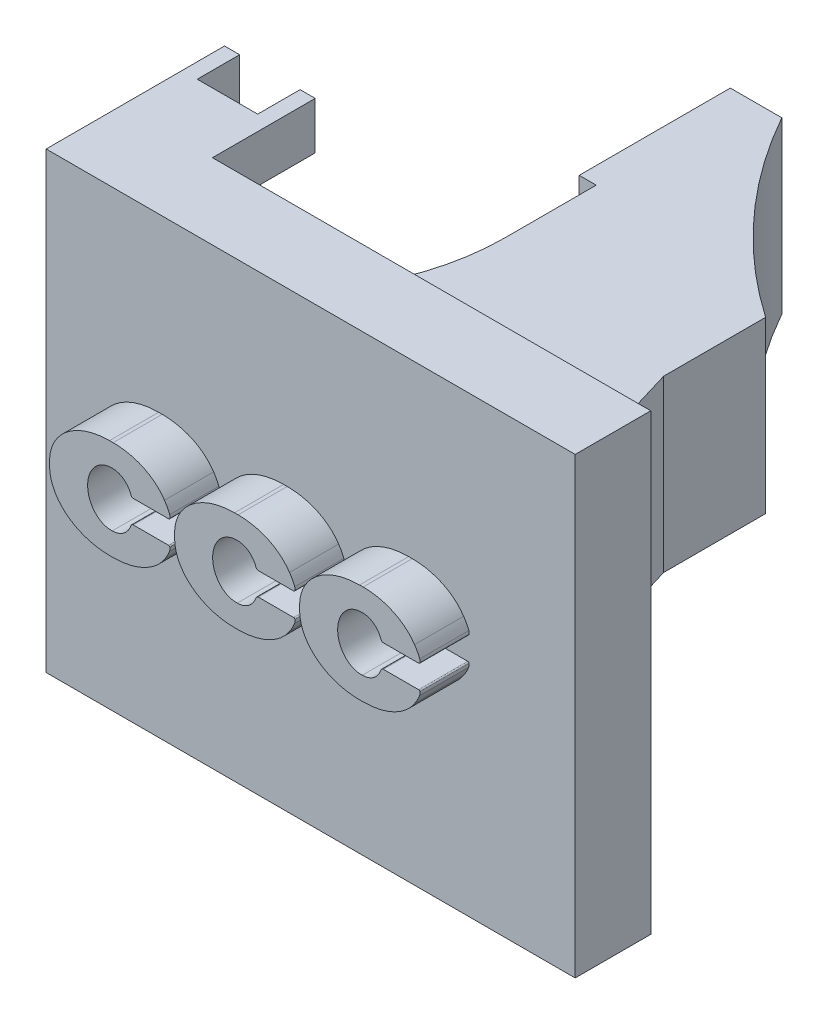
SolidWorks part; units mm, degrees
ref_plane "Front Plane" through (0, 0, 0) normal (0, 0, 1) x (1, 0, 0)
ref_plane "Top Plane" through (0, 0, 0) normal (0, 1, 0) x (1, 0, 0)
ref_plane "Right Plane" through (0, 0, 0) normal (1, 0, 0) x (0, 0, -1)
sketch "Sketch1" plane through (0, 0, 0) normal (0, 0, 1) x (1, 0, 0)
  line L1 (-7.5, 6) -> (7.5, 6)
  line L2 (-7.5, 6) -> (-7.5, -6)
  line L3 (-7.5, -6) -> (7.5, -6)
  line L4 (7.5, 6) -> (7.5, -6)
  line L5 (-7.5, 6) -> (7.5, -6) construction
  line L6 (-7.5, -6) -> (7.5, 6) construction
  point P0 (0, 0)
  dimension "D1" = 15
  dimension "D2" = 12
extrude "Boss-Extrude1" add sketch "Sketch1" along normal blind 2
sketch "Sketch2" plane through (0, 0, 2) normal (0, 0, 1) x (1, 0, 0)
  line L0 (-0.5835, 0.4438) -> (0.3524, 0.4438)
  line L1 (-1.1209, 1.4546) -> (-1.2145, 1.4546)
  line L2 (-2.8001, 0.2034) -> (-2.8001, 0.0733)
  line L3 (-1.2145, -1.1779) -> (-1.1209, -1.1779)
  line L4 (0.3478, -0.1633) -> (-0.5835, -0.1633)
  line L5 (-3.8918, 0.4438) -> (-2.956, 0.4438)
  line L6 (-4.4292, 1.4546) -> (-4.5228, 1.4546)
  line L7 (-6.1084, 0.2034) -> (-6.1084, 0.0733)
  line L8 (-4.5228, -1.1779) -> (-4.4292, -1.1779)
  line L9 (-2.9605, -0.1633) -> (-3.8918, -0.1633)
  line L10 (2.7248, 0.4438) -> (3.6607, 0.4438)
  line L11 (2.1874, 1.4546) -> (2.0938, 1.4546)
  line L12 (0.5082, 0.2034) -> (0.5082, 0.0733)
  line L13 (2.0938, -1.1779) -> (2.1874, -1.1779)
  line L14 (3.6561, -0.1633) -> (2.7248, -0.1633)
  arc A0 (-0.6452, 0.4874) -> (-0.5835, 0.4438) centre (-0.5835, 0.5092) ccw
  arc A1 (0.3524, 0.4438) -> (0.3816, 0.4686) centre (0.3479, 0.4787) ccw
  arc A2 (0.3816, 0.4686) -> (0.3774, 0.5561) centre (0.201, 0.5038) ccw
  arc A3 (0.3774, 0.5561) -> (0.2402, 0.8134) centre (-0.7046, 0.1445) ccw
  arc A4 (0.2402, -0.5368) -> (0.3727, -0.2904) centre (-0.6952, 0.1249) ccw
  arc A5 (0.3727, -0.2904) -> (0.3825, -0.1925) centre (0.2012, -0.2237) ccw
  arc A6 (0.3825, -0.1925) -> (0.3478, -0.1633) centre (0.3478, -0.1984) ccw
  arc A7 (-0.5835, -0.1633) -> (-0.6452, -0.2069) centre (-0.5835, -0.2287) ccw
  arc A8 (-3.9535, 0.4874) -> (-3.8918, 0.4438) centre (-3.8918, 0.5092) ccw
  arc A9 (-2.956, 0.4438) -> (-2.9267, 0.4686) centre (-2.9604, 0.4787) ccw
  arc A10 (-2.9267, 0.4686) -> (-2.9309, 0.5561) centre (-3.1073, 0.5038) ccw
  arc A11 (-2.9309, 0.5561) -> (-3.0681, 0.8134) centre (-4.0129, 0.1445) ccw
  arc A12 (-3.0681, -0.5368) -> (-2.9356, -0.2904) centre (-4.0035, 0.1249) ccw
  arc A13 (-2.9356, -0.2904) -> (-2.9258, -0.1925) centre (-3.1071, -0.2237) ccw
  arc A14 (-2.9258, -0.1925) -> (-2.9605, -0.1633) centre (-2.9605, -0.1984) ccw
  arc A15 (-3.8918, -0.1633) -> (-3.9535, -0.2069) centre (-3.8918, -0.2287) ccw
  arc A16 (2.6631, 0.4874) -> (2.7248, 0.4438) centre (2.7248, 0.5092) ccw
  arc A17 (3.6607, 0.4438) -> (3.6899, 0.4686) centre (3.6562, 0.4787) ccw
  arc A18 (3.6899, 0.4686) -> (3.6857, 0.5561) centre (3.5093, 0.5038) ccw
  arc A19 (3.6857, 0.5561) -> (3.5485, 0.8134) centre (2.6037, 0.1445) ccw
  arc A20 (3.5485, -0.5368) -> (3.681, -0.2904) centre (2.6131, 0.1249) ccw
  arc A21 (3.681, -0.2904) -> (3.6908, -0.1925) centre (3.5095, -0.2237) ccw
  arc A22 (3.6908, -0.1925) -> (3.6561, -0.1633) centre (3.6561, -0.1984) ccw
  arc A23 (2.7248, -0.1633) -> (2.6631, -0.2069) centre (2.7248, -0.2287) ccw
  ellipse E0 centre (-1.1734, 0.1385) end of major axis (-1.177, 0.8556) minor radius 0.6209 (-1.2015, 0.8549) -> (-1.1417, -0.5777) ccw
  ellipse E1 centre (-1.2295, 0.1385) end of major axis (-1.5121, -0.5431) minor radius 0.6039 (-0.6452, 0.4874) -> (-1.2015, 0.8549) ccw
  ellipse E2 centre (-1.2429, 0.1529) end of major axis (-2.8857, -0.0922) minor radius 1.2925 (0.2402, 0.8134) -> (-1.1209, 1.4546) ccw
  ellipse E3 centre (-1.1521, 0.1542) end of major axis (0.4928, 0.0248) minor radius 1.2979 (-1.2145, 1.4546) -> (-2.8001, 0.2034) ccw
  ellipse E4 centre (-1.1521, 0.1225) end of major axis (0.4928, 0.2518) minor radius 1.2979 (-2.8001, 0.0733) -> (-1.2145, -1.1779) ccw
  ellipse E5 centre (-1.2429, 0.1238) end of major axis (-2.8857, 0.3689) minor radius 1.2925 (-1.1209, -1.1779) -> (0.2402, -0.5368) ccw
  ellipse E6 centre (-1.2295, 0.1421) end of major axis (-0.9469, -0.5396) minor radius 0.6039 (-1.1417, -0.5777) -> (-0.6452, -0.2069) ccw
  ellipse E7 centre (-4.5378, 0.1385) end of major axis (-4.8204, -0.5431) minor radius 0.6039 (-3.9535, 0.4874) -> (-4.5098, 0.8549) ccw
  ellipse E8 centre (-4.5512, 0.1529) end of major axis (-6.194, -0.0922) minor radius 1.2925 (-3.0681, 0.8134) -> (-4.4292, 1.4546) ccw
  ellipse E9 centre (-4.4604, 0.1542) end of major axis (-6.1053, 0.2835) minor radius 1.2979 (-4.5228, 1.4546) -> (-6.1084, 0.2034) ccw
  ellipse E10 centre (-4.4604, 0.1225) end of major axis (-6.1053, -0.0069) minor radius 1.2979 (-6.1084, 0.0733) -> (-4.5228, -1.1779) ccw
  ellipse E11 centre (-4.5512, 0.1238) end of major axis (-6.194, 0.3689) minor radius 1.2925 (-4.4292, -1.1779) -> (-3.0681, -0.5368) ccw
  ellipse E12 centre (-4.5378, 0.1421) end of major axis (-4.2552, -0.5396) minor radius 0.6039 (-4.45, -0.5777) -> (-3.9535, -0.2069) ccw
  ellipse E13 centre (-4.4817, 0.1385) end of major axis (-4.4853, 0.8556) minor radius 0.6209 (-4.5098, 0.8549) -> (-4.45, -0.5777) ccw
  ellipse E14 centre (2.1349, 0.1385) end of major axis (2.1385, -0.5786) minor radius 0.6209 (2.1069, 0.8549) -> (2.1666, -0.5777) ccw
  ellipse E15 centre (2.0788, 0.1385) end of major axis (2.3614, 0.8201) minor radius 0.6039 (2.6631, 0.4874) -> (2.1069, 0.8549) ccw
  ellipse E16 centre (2.0654, 0.1529) end of major axis (3.7082, 0.3981) minor radius 1.2925 (3.5485, 0.8134) -> (2.1874, 1.4546) ccw
  ellipse E17 centre (2.1562, 0.1542) end of major axis (0.5113, 0.2835) minor radius 1.2979 (2.0938, 1.4546) -> (0.5082, 0.2034) ccw
  ellipse E18 centre (2.1562, 0.1225) end of major axis (3.8011, 0.2518) minor radius 1.2979 (0.5082, 0.0733) -> (2.0938, -1.1779) ccw
  ellipse E19 centre (2.0654, 0.1238) end of major axis (0.4226, 0.3689) minor radius 1.2925 (2.1874, -1.1779) -> (3.5485, -0.5368) ccw
  ellipse E20 centre (2.0788, 0.1421) end of major axis (2.3614, -0.5396) minor radius 0.6039 (2.1666, -0.5777) -> (2.6631, -0.2069) ccw
extrude "Boss-Extrude2" add sketch "Sketch2" along normal blind 2
sketch "Sketch3" plane through (0, 0, 0) normal (0, 1, 0) x (1, 0, 0)
  line L0 (7.5, 0) -> (-7.5, 0) construction
  line L1 (-5.267, 0.6593) -> (-4.0407, 2.642)
  line L2 (-3.1435, 5.7982) -> (-3.1435, 7.8852)
  line L3 (2.1273, 7.8852) -> (2.1273, 4.7149)
  line L4 (3.2287, 0) -> (3.2287, 1.0429)
  line L5 (2.1273, 4.7149) -> (3.2287, 1.0429)
  line L6 (-5.267, 0) -> (-5.267, 0.6593)
  line L7 (-1.1926, -2) -> (-1.1926, 1.9881) construction
  line L9 (-5.267, 0) -> (3.2287, 0)
  line L11 (-3.1435, 7.8852) -> (-3.1435, 12.1994)
  line L12 (-3.1435, 12.1994) -> (2.1273, 12.1994)
  line L16 (2.1273, 12.1994) -> (2.1273, 7.8852)
  arc A0 (-4.0407, 2.642) -> (-3.1435, 5.7982) centre (-9.1435, 5.7982) ccw
  dimension "D1" = 6
extrude "Boss-Extrude3" add sketch "Sketch3" along normal mid plane 4.5
sketch "Sketch4" plane through (7.5, 0, 0) normal (1, 0, 0) x (0, 0, -1)
  line L4 (0, -6) -> (0, 6)
  line L5 (0, 6) -> (-2, 6)
  line L6 (-2, 6) -> (-2, -6)
  line L7 (-2, -6) -> (0, -6)
  line L8 (0, -6) -> (0, 6)
  line L9 (0, 6) -> (-2, 6)
  line L10 (-2, 6) -> (-2, -6)
  line L11 (-2, -6) -> (0, -6)
  dimension "D1" = 0
extrude "Cut-Extrude1" cut sketch "Sketch4" against normal blind 1
sketch "Sketch6" plane through (0, 0, 4) normal (0, 0, 1) x (1, 0, 0)
  line L0 (2.7248, 0.4438) -> (3.6607, 0.4438) construction
  line L1 (2.1874, 1.4546) -> (2.0938, 1.4546) construction
  line L2 (0.5082, 0.2034) -> (0.5082, 0.0733) construction
  line L3 (2.0938, -1.1779) -> (2.1874, -1.1779) construction
  line L4 (3.6561, -0.1633) -> (2.7248, -0.1633) construction
  line L5 (-0.5835, 0.4438) -> (0.3524, 0.4438) construction
  line L6 (-1.1209, 1.4546) -> (-1.2145, 1.4546) construction
  line L7 (-2.8001, 0.2034) -> (-2.8001, 0.0733) construction
  line L8 (-1.2145, -1.1779) -> (-1.1209, -1.1779) construction
  line L9 (0.3478, -0.1633) -> (-0.5835, -0.1633) construction
  line L10 (-3.8918, 0.4438) -> (-2.956, 0.4438) construction
  line L11 (-4.4292, 1.4546) -> (-4.5228, 1.4546) construction
  line L12 (-6.1084, 0.2034) -> (-6.1084, 0.0733) construction
  line L13 (-4.5228, -1.1779) -> (-4.4292, -1.1779) construction
  line L14 (-2.9605, -0.1633) -> (-3.8918, -0.1633) construction
  line L15 (2.7248, 0.4438) -> (3.6607, 0.4438)
  line L16 (2.1874, 1.4546) -> (2.0938, 1.4546)
  line L17 (0.5082, 0.2034) -> (0.5082, 0.0733)
  line L18 (2.0938, -1.1779) -> (2.1874, -1.1779)
  line L19 (3.6561, -0.1633) -> (2.7248, -0.1633)
  line L20 (-0.5835, 0.4438) -> (0.3524, 0.4438)
  line L21 (-1.1209, 1.4546) -> (-1.2145, 1.4546)
  line L22 (-2.8001, 0.2034) -> (-2.8001, 0.0733)
  line L23 (-1.2145, -1.1779) -> (-1.1209, -1.1779)
  line L24 (0.3478, -0.1633) -> (-0.5835, -0.1633)
  line L25 (-3.8918, 0.4438) -> (-2.956, 0.4438)
  line L26 (-4.4292, 1.4546) -> (-4.5228, 1.4546)
  line L27 (-6.1084, 0.2034) -> (-6.1084, 0.0733)
  line L28 (-4.5228, -1.1779) -> (-4.4292, -1.1779)
  line L29 (-2.9605, -0.1633) -> (-3.8918, -0.1633)
  arc A0 (2.6631, 0.4874) -> (2.7248, 0.4438) centre (2.7248, 0.5092) ccw construction
  arc A1 (3.6607, 0.4438) -> (3.6899, 0.4686) centre (3.6562, 0.4787) ccw construction
  arc A2 (3.6899, 0.4686) -> (3.6857, 0.5561) centre (3.5093, 0.5038) ccw construction
  arc A3 (3.6857, 0.5561) -> (3.5485, 0.8134) centre (2.6037, 0.1445) ccw construction
  arc A4 (3.5485, -0.5368) -> (3.681, -0.2904) centre (2.6131, 0.1249) ccw construction
  arc A5 (3.681, -0.2904) -> (3.6908, -0.1925) centre (3.5095, -0.2237) ccw construction
  arc A6 (3.6908, -0.1925) -> (3.6561, -0.1633) centre (3.6561, -0.1984) ccw construction
  arc A7 (2.7248, -0.1633) -> (2.6631, -0.2069) centre (2.7248, -0.2287) ccw construction
  arc A8 (-0.6452, 0.4874) -> (-0.5835, 0.4438) centre (-0.5835, 0.5092) ccw construction
  arc A9 (0.3524, 0.4438) -> (0.3816, 0.4686) centre (0.3479, 0.4787) ccw construction
  arc A10 (0.3816, 0.4686) -> (0.3774, 0.5561) centre (0.201, 0.5038) ccw construction
  arc A11 (0.3774, 0.5561) -> (0.2402, 0.8134) centre (-0.7046, 0.1445) ccw construction
  arc A12 (0.2402, -0.5368) -> (0.3727, -0.2904) centre (-0.6952, 0.1249) ccw construction
  arc A13 (0.3727, -0.2904) -> (0.3825, -0.1925) centre (0.2012, -0.2237) ccw construction
  arc A14 (0.3825, -0.1925) -> (0.3478, -0.1633) centre (0.3478, -0.1984) ccw construction
  arc A15 (-0.5835, -0.1633) -> (-0.6452, -0.2069) centre (-0.5835, -0.2287) ccw construction
  arc A16 (-3.9535, 0.4874) -> (-3.8918, 0.4438) centre (-3.8918, 0.5092) ccw construction
  arc A17 (-2.956, 0.4438) -> (-2.9267, 0.4686) centre (-2.9604, 0.4787) ccw construction
  arc A18 (-2.9267, 0.4686) -> (-2.9309, 0.5561) centre (-3.1073, 0.5038) ccw construction
  arc A19 (-2.9309, 0.5561) -> (-3.0681, 0.8134) centre (-4.0129, 0.1445) ccw construction
  arc A20 (-3.0681, -0.5368) -> (-2.9356, -0.2904) centre (-4.0035, 0.1249) ccw construction
  arc A21 (-2.9356, -0.2904) -> (-2.9258, -0.1925) centre (-3.1071, -0.2237) ccw construction
  arc A22 (-2.9258, -0.1925) -> (-2.9605, -0.1633) centre (-2.9605, -0.1984) ccw construction
  arc A23 (-3.8918, -0.1633) -> (-3.9535, -0.2069) centre (-3.8918, -0.2287) ccw construction
  arc A24 (2.6631, 0.4874) -> (2.7248, 0.4438) centre (2.7248, 0.5092) ccw
  arc A25 (3.6607, 0.4438) -> (3.6899, 0.4686) centre (3.6562, 0.4787) ccw
  arc A26 (3.6899, 0.4686) -> (3.6857, 0.5561) centre (3.5093, 0.5038) ccw
  arc A27 (3.6857, 0.5561) -> (3.5485, 0.8134) centre (2.6037, 0.1445) ccw
  arc A28 (3.5485, -0.5368) -> (3.681, -0.2904) centre (2.6131, 0.1249) ccw
  arc A29 (3.681, -0.2904) -> (3.6908, -0.1925) centre (3.5095, -0.2237) ccw
  arc A30 (3.6908, -0.1925) -> (3.6561, -0.1633) centre (3.6561, -0.1984) ccw
  arc A31 (2.7248, -0.1633) -> (2.6631, -0.2069) centre (2.7248, -0.2287) ccw
  arc A32 (-0.6452, 0.4874) -> (-0.5835, 0.4438) centre (-0.5835, 0.5092) ccw
  arc A33 (0.3524, 0.4438) -> (0.3816, 0.4686) centre (0.3479, 0.4787) ccw
  arc A34 (0.3816, 0.4686) -> (0.3774, 0.5561) centre (0.201, 0.5038) ccw
  arc A35 (0.3774, 0.5561) -> (0.2402, 0.8134) centre (-0.7046, 0.1445) ccw
  arc A36 (0.2402, -0.5368) -> (0.3727, -0.2904) centre (-0.6952, 0.1249) ccw
  arc A37 (0.3727, -0.2904) -> (0.3825, -0.1925) centre (0.2012, -0.2237) ccw
  arc A38 (0.3825, -0.1925) -> (0.3478, -0.1633) centre (0.3478, -0.1984) ccw
  arc A39 (-0.5835, -0.1633) -> (-0.6452, -0.2069) centre (-0.5835, -0.2287) ccw
  arc A40 (-3.9535, 0.4874) -> (-3.8918, 0.4438) centre (-3.8918, 0.5092) ccw
  arc A41 (-2.956, 0.4438) -> (-2.9267, 0.4686) centre (-2.9604, 0.4787) ccw
  arc A42 (-2.9267, 0.4686) -> (-2.9309, 0.5561) centre (-3.1073, 0.5038) ccw
  arc A43 (-2.9309, 0.5561) -> (-3.0681, 0.8134) centre (-4.0129, 0.1445) ccw
  arc A44 (-3.0681, -0.5368) -> (-2.9356, -0.2904) centre (-4.0035, 0.1249) ccw
  arc A45 (-2.9356, -0.2904) -> (-2.9258, -0.1925) centre (-3.1071, -0.2237) ccw
  arc A46 (-2.9258, -0.1925) -> (-2.9605, -0.1633) centre (-2.9605, -0.1984) ccw
  arc A47 (-3.8918, -0.1633) -> (-3.9535, -0.2069) centre (-3.8918, -0.2287) ccw
  ellipse E0 centre (2.0788, 0.1385) end of major axis (1.7962, -0.5431) minor radius 0.6039 (2.6631, 0.4874) -> (2.1069, 0.8549) ccw construction
  ellipse E1 centre (2.0654, 0.1529) end of major axis (0.4226, -0.0922) minor radius 1.2925 (3.5485, 0.8134) -> (2.1874, 1.4546) ccw construction
  ellipse E2 centre (2.1562, 0.1542) end of major axis (0.5113, 0.2835) minor radius 1.2979 (2.0938, 1.4546) -> (0.5082, 0.2034) ccw construction
  ellipse E3 centre (2.1562, 0.1225) end of major axis (3.8011, 0.2518) minor radius 1.2979 (0.5082, 0.0733) -> (2.0938, -1.1779) ccw construction
  ellipse E4 centre (2.0654, 0.1238) end of major axis (0.4226, 0.3689) minor radius 1.2925 (2.1874, -1.1779) -> (3.5485, -0.5368) ccw construction
  ellipse E5 centre (2.0788, 0.1421) end of major axis (2.3614, -0.5396) minor radius 0.6039 (2.1666, -0.5777) -> (2.6631, -0.2069) ccw construction
  ellipse E6 centre (2.1349, 0.1385) end of major axis (2.1385, -0.5786) minor radius 0.6209 (2.1069, 0.8549) -> (2.1666, -0.5777) ccw construction
  ellipse E7 centre (-1.2295, 0.1385) end of major axis (-1.5121, -0.5431) minor radius 0.6039 (-0.6452, 0.4874) -> (-1.2015, 0.8549) ccw construction
  ellipse E8 centre (-1.2429, 0.1529) end of major axis (0.3999, 0.3981) minor radius 1.2925 (0.2402, 0.8134) -> (-1.1209, 1.4546) ccw construction
  ellipse E9 centre (-1.1521, 0.1542) end of major axis (-2.797, 0.2835) minor radius 1.2979 (-1.2145, 1.4546) -> (-2.8001, 0.2034) ccw construction
  ellipse E10 centre (-1.1521, 0.1225) end of major axis (0.4928, 0.2518) minor radius 1.2979 (-2.8001, 0.0733) -> (-1.2145, -1.1779) ccw construction
  ellipse E11 centre (-1.2429, 0.1238) end of major axis (0.3999, -0.1214) minor radius 1.2925 (-1.1209, -1.1779) -> (0.2402, -0.5368) ccw construction
  ellipse E12 centre (-1.2295, 0.1421) end of major axis (-0.9469, -0.5396) minor radius 0.6039 (-1.1417, -0.5777) -> (-0.6452, -0.2069) ccw construction
  ellipse E13 centre (-1.1734, 0.1385) end of major axis (-1.1698, -0.5786) minor radius 0.6209 (-1.2015, 0.8549) -> (-1.1417, -0.5777) ccw construction
  ellipse E14 centre (-4.5378, 0.1385) end of major axis (-4.8204, -0.5431) minor radius 0.6039 (-3.9535, 0.4874) -> (-4.5098, 0.8549) ccw construction
  ellipse E15 centre (-4.5512, 0.1529) end of major axis (-2.9084, 0.3981) minor radius 1.2925 (-3.0681, 0.8134) -> (-4.4292, 1.4546) ccw construction
  ellipse E16 centre (-4.4604, 0.1542) end of major axis (-6.1053, 0.2835) minor radius 1.2979 (-4.5228, 1.4546) -> (-6.1084, 0.2034) ccw construction
  ellipse E17 centre (-4.4604, 0.1225) end of major axis (-2.8155, 0.2518) minor radius 1.2979 (-6.1084, 0.0733) -> (-4.5228, -1.1779) ccw construction
  ellipse E18 centre (-4.5512, 0.1238) end of major axis (-6.194, 0.3689) minor radius 1.2925 (-4.4292, -1.1779) -> (-3.0681, -0.5368) ccw construction
  ellipse E19 centre (-4.5378, 0.1421) end of major axis (-4.2552, -0.5396) minor radius 0.6039 (-4.45, -0.5777) -> (-3.9535, -0.2069) ccw construction
  ellipse E20 centre (-4.4817, 0.1385) end of major axis (-4.4781, -0.5786) minor radius 0.6209 (-4.5098, 0.8549) -> (-4.45, -0.5777) ccw construction
  ellipse E21 centre (2.0788, 0.1385) end of major axis (1.7962, -0.5431) minor radius 0.6039 (2.6631, 0.4874) -> (2.1069, 0.8549) ccw
  ellipse E22 centre (2.0654, 0.1529) end of major axis (3.7082, 0.3981) minor radius 1.2925 (3.5485, 0.8134) -> (2.1874, 1.4546) ccw
  ellipse E23 centre (2.1562, 0.1542) end of major axis (0.5113, 0.2835) minor radius 1.2979 (2.0938, 1.4546) -> (0.5082, 0.2034) ccw
  ellipse E24 centre (2.1562, 0.1225) end of major axis (3.8011, 0.2518) minor radius 1.2979 (0.5082, 0.0733) -> (2.0938, -1.1779) ccw
  ellipse E25 centre (2.0654, 0.1238) end of major axis (0.4226, 0.3689) minor radius 1.2925 (2.1874, -1.1779) -> (3.5485, -0.5368) ccw
  ellipse E26 centre (2.0788, 0.1421) end of major axis (2.3614, -0.5396) minor radius 0.6039 (2.1666, -0.5777) -> (2.6631, -0.2069) ccw
  ellipse E27 centre (2.1349, 0.1385) end of major axis (2.1385, -0.5786) minor radius 0.6209 (2.1069, 0.8549) -> (2.1666, -0.5777) ccw
  ellipse E28 centre (-1.2295, 0.1385) end of major axis (-1.5121, -0.5431) minor radius 0.6039 (-0.6452, 0.4874) -> (-1.2015, 0.8549) ccw
  ellipse E29 centre (-1.2429, 0.1529) end of major axis (0.3999, 0.3981) minor radius 1.2925 (0.2402, 0.8134) -> (-1.1209, 1.4546) ccw
  ellipse E30 centre (-1.1521, 0.1542) end of major axis (-2.797, 0.2835) minor radius 1.2979 (-1.2145, 1.4546) -> (-2.8001, 0.2034) ccw
  ellipse E31 centre (-1.1521, 0.1225) end of major axis (0.4928, 0.2518) minor radius 1.2979 (-2.8001, 0.0733) -> (-1.2145, -1.1779) ccw
  ellipse E32 centre (-1.2429, 0.1238) end of major axis (-2.8857, 0.3689) minor radius 1.2925 (-1.1209, -1.1779) -> (0.2402, -0.5368) ccw
  ellipse E33 centre (-1.2295, 0.1421) end of major axis (-0.9469, -0.5396) minor radius 0.6039 (-1.1417, -0.5777) -> (-0.6452, -0.2069) ccw
  ellipse E34 centre (-1.1734, 0.1385) end of major axis (-1.1698, -0.5786) minor radius 0.6209 (-1.2015, 0.8549) -> (-1.1417, -0.5777) ccw
  ellipse E35 centre (-4.5378, 0.1385) end of major axis (-4.8204, -0.5431) minor radius 0.6039 (-3.9535, 0.4874) -> (-4.5098, 0.8549) ccw
  ellipse E36 centre (-4.5512, 0.1529) end of major axis (-2.9084, 0.3981) minor radius 1.2925 (-3.0681, 0.8134) -> (-4.4292, 1.4546) ccw
  ellipse E37 centre (-4.4604, 0.1542) end of major axis (-6.1053, 0.2835) minor radius 1.2979 (-4.5228, 1.4546) -> (-6.1084, 0.2034) ccw
  ellipse E38 centre (-4.4604, 0.1225) end of major axis (-2.8155, 0.2518) minor radius 1.2979 (-6.1084, 0.0733) -> (-4.5228, -1.1779) ccw
  ellipse E39 centre (-4.5512, 0.1238) end of major axis (-6.194, 0.3689) minor radius 1.2925 (-4.4292, -1.1779) -> (-3.0681, -0.5368) ccw
  ellipse E40 centre (-4.5378, 0.1421) end of major axis (-4.2552, -0.5396) minor radius 0.6039 (-4.45, -0.5777) -> (-3.9535, -0.2069) ccw
  ellipse E41 centre (-4.4817, 0.1385) end of major axis (-4.4781, -0.5786) minor radius 0.6209 (-4.5098, 0.8549) -> (-4.45, -0.5777) ccw
extrude "Cut-Extrude3" cut sketch "Sketch6" against normal blind 0.7
sketch "Sketch7" plane through (-3.1435, 0, 0) normal (-1, 0, 0) x (0, 0, 1)
  line L0 (-12.1994, -2.25) -> (-5.7982, -2.25) construction
  line L1 (-12.1994, 2.25) -> (-8.1994, 2.25)
  line L2 (-12.1994, 2.25) -> (-12.1994, -2.25)
  line L3 (-12.1994, -2.25) -> (-8.1994, -2.25)
  line L4 (-8.1994, 2.25) -> (-8.1994, -2.25)
  dimension "D1" = 4
extrude "Boss-Extrude4" add sketch "Sketch7" along normal blind 0.45
sketch "Sketch8" plane through (0, 6, 0) normal (0, 1, 0) x (1, 0, 0)
  line L0 (-7.5, 0) -> (-7.5, 2.7203)
  line L1 (-7.5, 2.7203) -> (-7.1, 2.7203)
  line L2 (-7.1, 2.7203) -> (-7.1, 0)
  line L3 (6.5, 0) -> (-7.5, 0) construction
  line L4 (-7.1, 0) -> (-7.5, 0)
  line L6 (-5.1, 2.7203) -> (-5.5, 2.7203)
  line L7 (-5.1, 2.7203) -> (-5.1, 0)
  line L8 (-5.1, 0) -> (-5.5, 0)
  line L9 (-5.5, 2.7203) -> (-5.5, 0)
  dimension "D1" = 0.4
  dimension "D2" = 1.6
  dimension "D3" = 0.4
extrude "Boss-Extrude5" add sketch "Sketch8" against normal blind 1.25
pattern_linear "LPattern1" count 2 spacing 10.75 along (0, -1, 0) of "Boss-Extrude5"
sketch "Sketch11" plane through (0, 2.25, 0) normal (0, 1, 0) x (1, 0, 0)
  line L0 (2.1273, 12.1994) -> (-3.5935, 12.1994) construction
  line L2 (-2.2306, 12.1994) -> (2.1273, 12.1994)
  line L3 (2.1273, 12.1994) -> (2.1273, 7.4129)
  line L4 (2.1273, 4.7149) -> (2.1273, 12.1994) construction
  arc A0 (-2.2306, 12.1994) -> (2.1273, 7.4129) centre (10.2386, 19.1749) ccw
extrude "Cut-Extrude4" cut sketch "Sketch11" against normal up to surface (4.5 mm away) up to face at (-1.5561, -2.25, -5.0539)
sketch "Sketch12" plane through (0, 6, 0) normal (0, 1, 0) x (1, 0, 0)
  line L2 (-5.5, 0) -> (-7.1, 0)
  line L3 (-5.5, 0) -> (-5.5, 1.598)
  line L4 (-5.5, 1.598) -> (-7.1, 1.598)
  line L5 (-7.1, 0) -> (-7.1, 1.598)
  line L6 (-7.1, 0) -> (-7.1, 2.7203) construction
extrude "Boss-Extrude10" add sketch "Sketch12" against normal up to surface (9.5 mm away)
sketch "Sketch13" plane through (0, -6, 0) normal (0, -1, 0) x (1, 0, 0)
  line L0 (-7.1, 0) -> (-7.1, -2.7203) construction
  line L1 (-7.1, -1.598) -> (-5.5, -1.598)
  line L2 (-7.1, -1.598) -> (-7.1, 0)
  line L3 (-7.1, 0) -> (-5.5, 0)
  line L4 (-5.5, -1.598) -> (-5.5, 0)
  line L5 (-5.5, -1.598) -> (-7.1, -1.598) construction
extrude "Boss-Extrude11" add sketch "Sketch13" against normal up to surface (1.25 mm away) up to face at (-7.3, -4.75, -1.3601)
